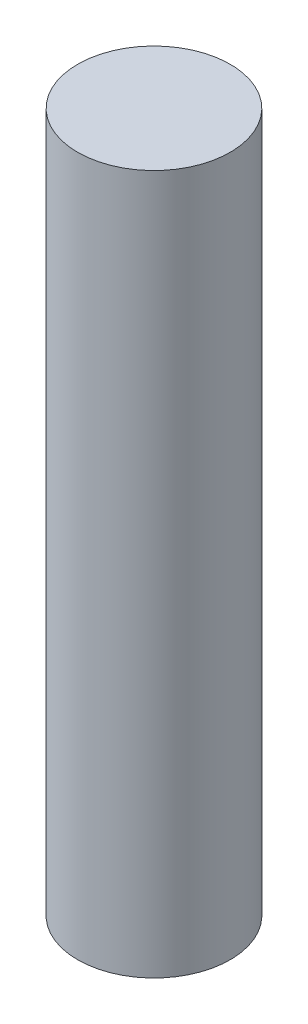
SolidWorks part; units mm, degrees
ref_plane "Front Plane" through (0, 0, 0) normal (0, 0, 1) x (1, 0, 0)
ref_plane "Top Plane" through (0, 0, 0) normal (0, 1, 0) x (1, 0, 0)
ref_plane "Right Plane" through (0, 0, 0) normal (1, 0, 0) x (0, 0, -1)
sketch "Sketch1" plane through (0, 0, 0) normal (0, 1, 0) x (1, 0, 0)
  circle A0 centre (0, 0) radius 3
extrude "Boss-Extrude2" add sketch "Sketch1" along normal blind 27.5
